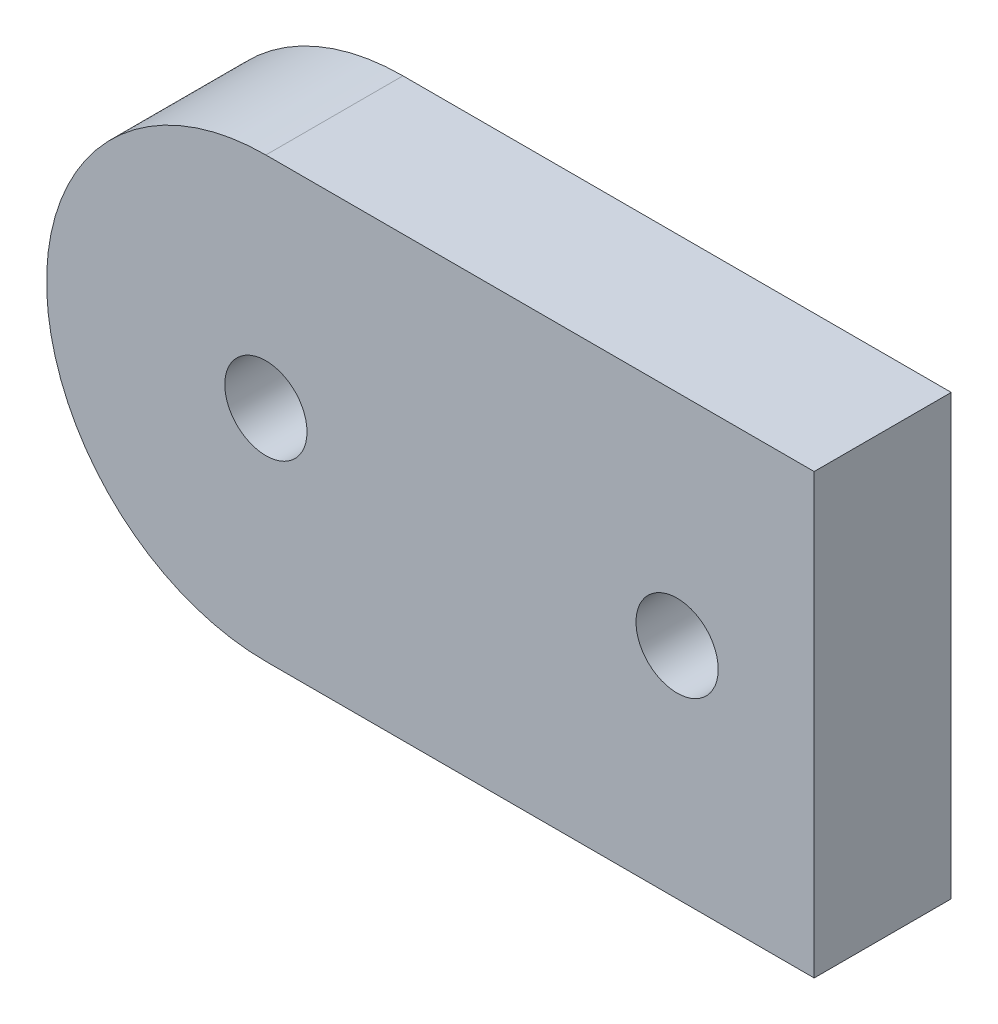
SolidWorks part; units mm, degrees
ref_plane "Plan de face" through (0, 0, 0) normal (0, 0, 1) x (1, 0, 0)
ref_plane "Plan de dessus" through (0, 0, 0) normal (0, 1, 0) x (1, 0, 0)
ref_plane "Plan de droite" through (0, 0, 0) normal (1, 0, 0) x (0, 0, -1)
sketch "Esquisse1" plane through (0, 0, 0) normal (0, 0, 1) x (1, 0, 0)
  line L0 (0, 0) -> (80, 0) construction
  line L1 (20, 0) -> (20, 23.8674) construction
  line L2 (0, 0) -> (0, 35) construction
  line L3 (0, 35) -> (55, 35) construction
  line L4 (0, 8) -> (20, 8)
  line L5 (82.6316, 13.5175) -> (85, 11.6762) construction
  line L6 (20, 8) -> (32.7289, 8) construction
  line L7 (0, -8) -> (55, -8) construction
  line L8 (55, 35) -> (55, -8) construction
  line L9 (0, -8) -> (20, -8)
  line L10 (20, -8) -> (20, 8)
  circle A0 centre (0, 0) radius 1.5
  arc A1 (0, 8) -> (0, -8) centre (0, 0) ccw
  circle A2 centre (55, 35) radius 35 construction
  arc A3 (32.7289, 8) -> (82.6316, 13.5175) centre (55, 35) ccw construction
  arc A4 (82.6316, 13.5175) -> (87.5479, 10.0925) centre (85, 11.6762) cw construction
  arc A5 (55, -8) -> (87.5479, 10.0925) centre (55, 30.3227) ccw construction
  circle A6 centre (15, 0) radius 1.5
  dimension "D3" = 3
  dimension "D4" = 35
  dimension "D6" = 70
  dimension "D7" = 3
  dimension "D8" = 8
  dimension "D9" = 30
  dimension "D10" = 15
  dimension "D1" = 20
  dimension "D2" = 80
  dimension "D5" = 55
extrude "Boss.-Extru.1" add sketch "Esquisse1" along normal blind 5
